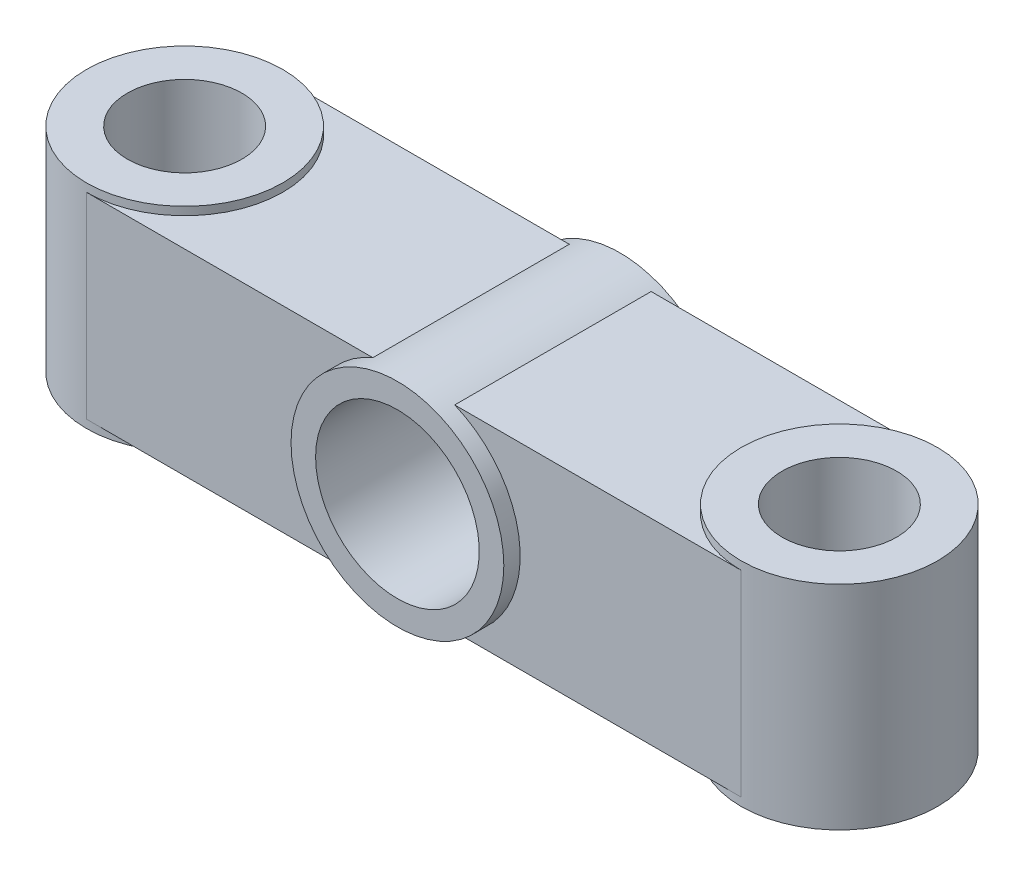
SolidWorks part; units mm, degrees
ref_plane "前视基准面" through (0, 0, 0) normal (0, 0, 1) x (1, 0, 0)
ref_plane "上视基准面" through (0, 0, 0) normal (0, 1, 0) x (1, 0, 0)
ref_plane "右视基准面" through (0, 0, 0) normal (1, 0, 0) x (0, 0, -1)
sketch "草图1" plane through (0, 0, 0) normal (0, 1, 0) x (1, 0, 0)
  line L1 (-10, -3) -> (10, -3)
  line L3 (-10, 3) -> (10, 3)
  line L5 (-13, -3) -> (13, 3) construction
  line L6 (-13, 3) -> (13, -3) construction
  arc A0 (10, -3) -> (10, 3) centre (10, 0) ccw
  arc A1 (-10, 3) -> (-10, -3) centre (-10, 0) ccw
  point P0 (0, 0)
  dimension "D3" = 6
  dimension "D4" = 6
  dimension "D1" = 26
  dimension "D2" = 6
extrude "拉伸1" add sketch "草图1" along normal mid plane 6
sketch "草图2" plane through (0, 0, 0) normal (0, 1, 0) x (1, 0, 0)
  circle A0 centre (10, 0) radius 3
  circle A1 centre (-10, 0) radius 3
extrude "拉伸2" add sketch "草图2" along normal mid plane 6.5
sketch "草图3" plane through (0, 3.25, 0) normal (0, 1, 0) x (1, 0, 0)
  circle A0 centre (-10, 0) radius 1.75
  circle A1 centre (10, 0) radius 1.75
  dimension "D1" = 3.5
  dimension "D2" = 3.5
extrude "拉伸3" cut sketch "草图3" against normal blind 6.5
sketch "草图4" plane through (0, 0, -3) normal (0, 0, -1) x (-1, 0, 0)
  line L0 (0, 3) -> (0, -3) construction
  line L1 (-10, 3) -> (10, 3) construction
  line L2 (-10, -3) -> (10, -3) construction
  circle A0 centre (0, 0) radius 3.25
  dimension "D1" = 6.5
extrude "拉伸5" add sketch "草图4" against normal blind 6.5
sketch "草图6" plane through (0, 0, -3) normal (0, 0, -1) x (-1, 0, 0)
  circle A0 centre (0, 0) radius 3.25
extrude "拉伸6" add sketch "草图6" along normal blind 0.3
sketch "草图7" plane through (0, 0, -3.3) normal (0, 0, -1) x (-1, 0, 0)
  circle A0 centre (0, 0) radius 2.5
  dimension "D1" = 5
extrude "拉伸7" cut sketch "草图7" against normal through all
